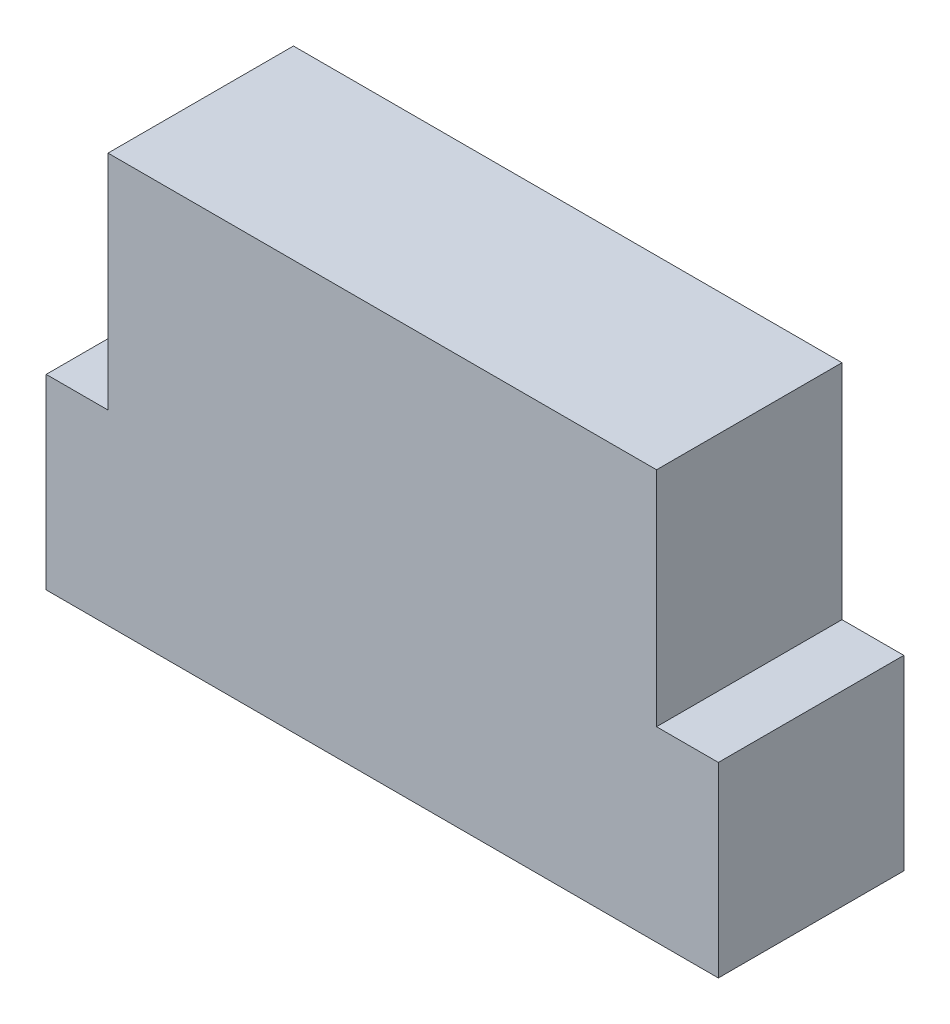
SolidWorks part; units mm, degrees
ref_plane "정면" through (0, 0, 0) normal (0, 0, 1) x (1, 0, 0)
ref_plane "윗면" through (0, 0, 0) normal (0, 1, 0) x (1, 0, 0)
ref_plane "우측면" through (0, 0, 0) normal (1, 0, 0) x (0, 0, -1)
sketch "스케치2" plane through (0, 0, 0) normal (0, 0, 1) x (1, 0, 0)
  line L0 (0, 0) -> (47.71, 0)
  line L1 (47.71, 0) -> (37.32, -17.996)
  line L2 (37.32, -17.996) -> (10.39, -17.996)
  line L3 (10.39, -17.996) -> (0, 0)
  dimension "D1" = 60
  dimension "D2" = 47.71
  dimension "D3" = 20.78
extrude "보스-돌출1" add sketch "스케치2" along normal blind 2
sketch "스케치3" plane through (0, 0, 2) normal (0, 0, 1) x (1, 0, 0)
  line L0 (23.855, 0) -> (23.855, -17.996)
  line L1 (47.71, 0) -> (0, 0) construction
  line L2 (10.39, -17.996) -> (37.32, -17.996) construction
  line L3 (23.855, -17.996) -> (23.855, -2.996)
  line L4 (42.5153, -2.996) -> (5.1947, -2.996)
  line L5 (5.1947, -2.996) -> (13.855, -17.996)
  line L6 (13.855, -17.996) -> (33.855, -17.996)
  line L7 (17.0871, -10.5941) -> (19.0871, -14.0582)
  line L8 (13.6229, -12.5941) -> (15.6229, -16.0582)
  line L9 (15.355, -4.996) -> (17.355, -4.996)
  line L10 (17.355, -8.996) -> (15.355, -8.996)
  line L11 (30.355, -8.996) -> (32.355, -8.996)
  line L12 (32.355, -4.996) -> (30.355, -4.996)
  line L13 (34.0871, -12.5941) -> (32.0871, -16.0582)
  line L14 (30.6229, -10.5941) -> (28.6229, -14.0582)
  line L15 (42.5153, -2.996) -> (33.855, -17.996)
  line L16 (33.855, -17.996) -> (37.32, -17.996)
  line L17 (37.32, -17.996) -> (47.71, 0)
  line L18 (47.71, 0) -> (0, 0)
  line L19 (0, 0) -> (10.39, -17.996)
  line L20 (10.39, -17.996) -> (13.855, -17.996)
  circle A0 centre (17.355, -15.0582) radius 2
  circle A1 centre (15.355, -11.5941) radius 2
  circle A2 centre (15.355, -6.996) radius 2
  circle A3 centre (17.355, -6.996) radius 2
  circle A4 centre (30.355, -6.996) radius 2
  circle A5 centre (32.355, -6.996) radius 2
  circle A6 centre (32.355, -11.5941) radius 2
  circle A7 centre (30.355, -15.0582) radius 2
  line M4 (47.71, 0) -> (0, 0)
  dimension "D4" = 4
  dimension "D8" = 4
  dimension "D1" = 15
  dimension "D2" = 60
  dimension "D3" = 10
  dimension "D5" = 2
  dimension "D6" = 2.5
  dimension "D7" = 6.5
  dimension "D9" = 2
  dimension "D11" = 2
sketch "스케치4" plane through (0, 0, 2) normal (0, 0, 1) x (1, 0, 0)
  line L0 (23.855, 2.0529) -> (23.855, -17.996)
  line L1 (23.855, -17.996) -> (23.855, -2.996)
  line L2 (42.5153, -2.996) -> (5.1947, -2.996)
  line L3 (5.1947, -2.996) -> (13.855, -17.996)
  line L4 (13.855, -17.996) -> (33.855, -17.996)
  line L5 (18.221, -12.5582) -> (19.0871, -14.0582)
  line L6 (14.7569, -14.5582) -> (15.6229, -16.0582)
  line L7 (15.855, -4.996) -> (16.855, -4.996)
  line L8 (16.855, -8.996) -> (15.855, -8.996)
  line L9 (30.855, -8.996) -> (31.855, -8.996)
  line L10 (31.855, -4.996) -> (30.855, -4.996)
  line L11 (32.9531, -14.5582) -> (32.0871, -16.0582)
  line L12 (29.489, -12.5582) -> (28.6229, -14.0582)
  line L13 (42.5153, -2.996) -> (33.855, -17.996)
  line L14 (33.855, -17.996) -> (37.32, -17.996)
  line L15 (37.32, -17.996) -> (47.71, 0)
  line L16 (47.71, 0) -> (0, 0)
  line L17 (0, 0) -> (10.39, -17.996)
  line L18 (10.39, -17.996) -> (13.855, -17.996)
  line L19 (10.39, -17.996) -> (0, 0)
  line L20 (47.71, 0) -> (37.32, -17.996)
  line L21 (13.7395, -17.996) -> (5.0215, -2.896)
  line L22 (5.0215, -2.896) -> (42.6885, -2.896)
  line L23 (42.6885, -2.896) -> (33.9705, -17.996)
  line L24 (42.6885, -2.896) -> (46.038, -2.896)
  line L25 (5.0215, -2.896) -> (1.672, -2.896)
  circle A0 centre (17.355, -15.0582) radius 2
  circle A1 centre (16.489, -13.5582) radius 2
  circle A2 centre (15.855, -6.996) radius 2
  circle A3 centre (16.855, -6.996) radius 2
  circle A4 centre (30.855, -6.996) radius 2
  circle A5 centre (31.855, -6.996) radius 2
  circle A6 centre (31.221, -13.5582) radius 2
  circle A7 centre (30.355, -15.0582) radius 2
  line M10 (10.39, -17.996) -> (37.32, -17.996)
  line M11 (37.32, -17.996) -> (47.71, 0)
  dimension "D4" = 4
  dimension "D8" = 4
  dimension "D1" = 15
  dimension "D2" = 60
  dimension "D3" = 10
  dimension "D5" = 1.7321
  dimension "D6" = 2.5
  dimension "D7" = 6.5
  dimension "D9" = 1
  dimension "D10" = 7
  dimension "D11" = 2
  dimension "D12" = 47.71
  dimension "D13" = 3.0008
  dimension "D14" = 2.996
  dimension "D15" = 0.1
  dimension "D16" = 0.1
  dimension "D17" = 0.1
extrude "보스-돌출5" add sketch "스케치4" along normal blind 12 contours L21 L25 L19 M10 | L24 L23 L14 M11
extrude "보스-돌출6" add sketch "스케치3" along normal blind 12 contours A1 | A6 M4
sketch "스케치5" plane through (0, 0, 2) normal (0, 0, 1) x (1, 0, 0)
  line L0 (0, 0) -> (47.71, 0)
  line L1 (47.71, 0) -> (46.038, -2.896)
  line L2 (46.038, -2.896) -> (1.672, -2.896)
  line L3 (1.672, -2.896) -> (0, 0)
extrude "컷-돌출1" cut sketch "스케치5" against normal blind 12
sketch "스케치6" plane through (0, -2.896, 0) normal (0, 1, 0) x (1, 0, 0)
  line L0 (5.0215, -14) -> (1.672, -14)
  line L1 (1.672, -14) -> (1.672, 0)
  line L2 (1.672, 0) -> (46.038, 0)
  line L3 (46.038, 0) -> (46.038, -14)
  line L4 (46.038, -14) -> (42.6885, -14)
  line L5 (42.6885, -14) -> (42.6885, -2)
  line L6 (42.6885, -14) -> (42.6885, -2) construction
  line L7 (42.6885, -2) -> (5.0215, -2)
  line L8 (5.0215, -2) -> (5.0215, -14)
extrude "보스-돌출7" add sketch "스케치6" along normal blind 15
sketch "스케치7" plane through (0, 12.104, 0) normal (0, 1, 0) x (1, 0, 0)
  line L1 (1.672, -14) -> (46.038, -14)
  line L2 (1.672, -14) -> (1.672, 0)
  line L3 (1.672, 0) -> (46.038, 0)
  line L4 (46.038, -14) -> (46.038, 0)
extrude "보스-돌출8" add sketch "스케치7" along normal blind 3
sketch "스케치9" plane through (0, 12.104, 0) normal (0, -1, 0) x (1, 0, 0)
  line L1 (5.195, 13) -> (42.515, 13)
  line L2 (5.195, 13) -> (5.195, 3)
  line L3 (5.195, 3) -> (42.515, 3)
  line L4 (42.515, 13) -> (42.515, 3)
  line L5 (23.855, 14) -> (23.855, 0) construction
  line L7 (5.0215, 14) -> (42.6885, 14) construction
  line L12 (42.6885, 14) -> (5.0215, 14)
  line L14 (10.39, 0) -> (37.32, 0) construction
  point P8 (23.855, 14)
  point P9 (23.855, 13)
  dimension "D1" = 10
  dimension "D2" = 37.32
  dimension "D3" = 1
extrude "컷-돌출3" cut sketch "스케치9" against normal blind 1 contours L5 L1 L2 L3 | L1 L5 L3 L4
sketch "스케치10" plane through (0, 0, 14) normal (0, 0, 1) x (1, 0, 0)
  line L0 (10.39, -17.996) -> (37.32, -17.996)
  line L12 (13.7395, -17.996) -> (5.0215, -2.896)
  line L13 (5.0215, -2.896) -> (5.0215, 12.104)
  line L14 (5.0215, 12.104) -> (42.6885, 12.104)
  line L15 (42.6885, 12.104) -> (42.6885, -2.896)
  line L16 (42.6885, -2.896) -> (33.9705, -17.996)
  line L17 (33.9705, -17.996) -> (37.32, -17.996)
  line L18 (37.32, -17.996) -> (46.038, -2.896)
  line L19 (46.038, -2.896) -> (46.038, 15.104)
  line L20 (46.038, 15.104) -> (1.672, 15.104)
  line L21 (1.672, 15.104) -> (1.672, -2.896)
  line L22 (1.672, -2.896) -> (10.39, -17.996)
  line L23 (10.39, -17.996) -> (13.7395, -17.996)
  line L30 (37.32, -17.996) -> (46.038, -2.896)
  line L31 (46.038, -2.896) -> (46.038, 15.104)
  line L32 (46.038, 15.104) -> (1.672, 15.104)
  line L33 (1.672, 15.104) -> (1.672, -2.896)
  line L34 (1.672, -2.896) -> (10.39, -17.996)
  dimension "D1" = 0
extrude "보스-돌출9" add sketch "스케치10" along normal blind 1
scale "축척1" scale about centroid uniform scaling yes scale factor 0.1
sketch "스케치11" plane through (21.6367, 0, 0) normal (-1, 0, 0) x (0, 0, 1)
  line L1 (6.0658, 0.2927) -> (7.5658, 0.2927)
  line L2 (6.0658, 0.2927) -> (6.0658, -1.2173)
  line L3 (6.0658, -1.2173) -> (7.5658, -1.2173)
  line L4 (7.5658, 0.2927) -> (7.5658, -1.2173)
extrude "보스-돌출10" add sketch "스케치11" along normal mid plane 1
sketch "스케치12" plane through (26.0733, 0, 0) normal (1, 0, 0) x (0, 0, -1)
  line L1 (-7.5658, 0.2927) -> (-6.0658, 0.2927)
  line L2 (-7.5658, 0.2927) -> (-7.5658, -1.2173)
  line L3 (-7.5658, -1.2173) -> (-6.0658, -1.2173)
  line L4 (-6.0658, 0.2927) -> (-6.0658, -1.2173)
extrude "보스-돌출11" add sketch "스케치12" along normal mid plane 1
sketch "스케치13" plane through (0, 0, 6.0658) normal (0, 0, -1) x (-1, 0, 0)
  line L1 (-26.5733, 0.2927) -> (-21.1367, 0.2927)
  line L2 (-26.5733, 0.2927) -> (-26.5733, -1.2173)
  line L3 (-26.5733, -1.2173) -> (-21.1367, -1.2173)
  line L4 (-21.1367, 0.2927) -> (-21.1367, -1.2173)
extrude "보스-돌출12" add sketch "스케치13" against normal blind 1.5
